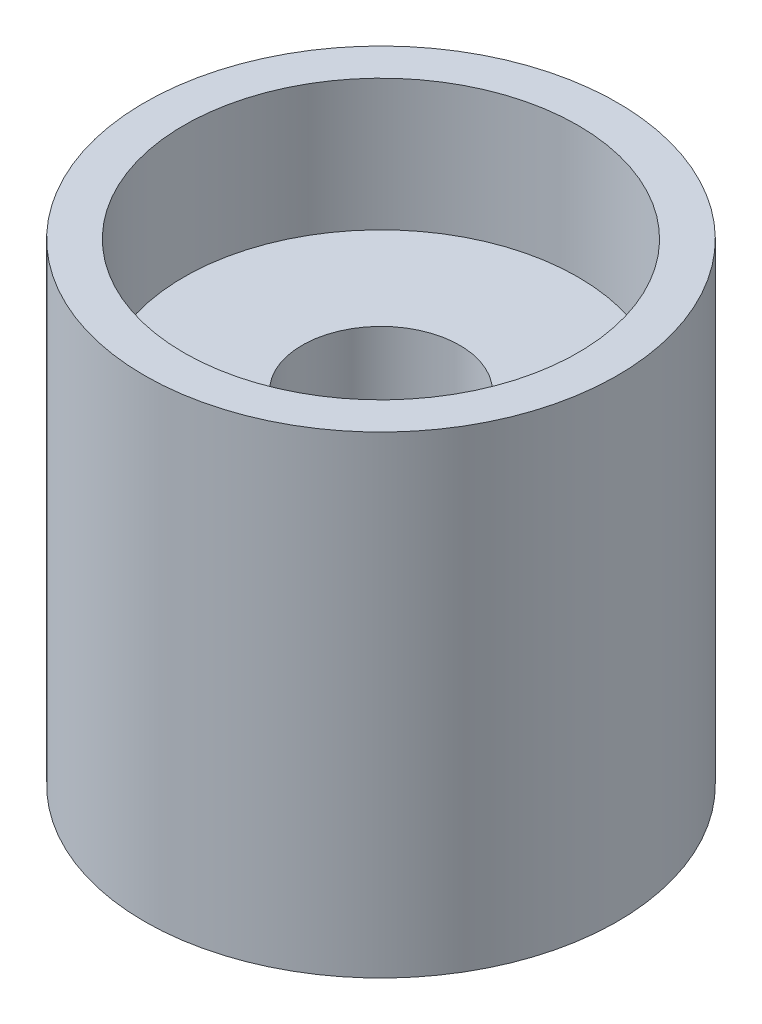
SolidWorks part; units mm, degrees
ref_plane "Front Plane" through (0, 0, 0) normal (0, 0, 1) x (1, 0, 0)
ref_plane "Top Plane" through (0, 0, 0) normal (0, 1, 0) x (1, 0, 0)
ref_plane "Right Plane" through (0, 0, 0) normal (1, 0, 0) x (0, 0, -1)
sketch "Sketch1" plane through (0, 0, 0) normal (0, 1, 0) x (1, 0, 0)
  circle A0 centre (0, 0) radius 9
  circle A1 centre (0, 0) radius 7.5
  dimension "D1" = 15
  dimension "D2" = 18
extrude "Boss-Extrude1" add sketch "Sketch1" along normal blind 18
ref_plane "Plane1" through (0, 9, 0) normal (0, 1, 0) x (1, 0, 0)
sketch "Sketch2" plane through (0, 9, 0) normal (0, 1, 0) x (1, 0, 0)
  circle A0 centre (0, 0) radius 7.5
  circle A1 centre (0, 0) radius 3
  dimension "D1" = 6
extrude "Boss-Extrude2" add sketch "Sketch2" along normal mid plane 8
